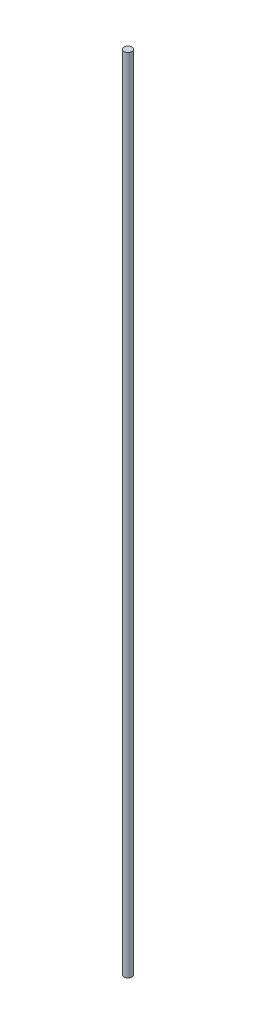
SolidWorks part; units mm, degrees
material "AISI 1020"
ref_plane "Front Plane" through (0, 0, 0) normal (0, 0, 1) x (1, 0, 0)
ref_plane "Top Plane" through (0, 0, 0) normal (0, 1, 0) x (1, 0, 0)
ref_plane "Right Plane" through (0, 0, 0) normal (1, 0, 0) x (0, 0, -1)
sketch "Sketch1" plane through (0, 0, 0) normal (0, 1, 0) x (1, 0, 0)
  circle A0 centre (0, 0) radius 4
  dimension "D1" = 8
extrude "Boss-Extrude1" add sketch "Sketch1" along normal blind 415 and the other way blind 400
cosmetic thread "Cosmetic Thread1" parameters "D2"=7
